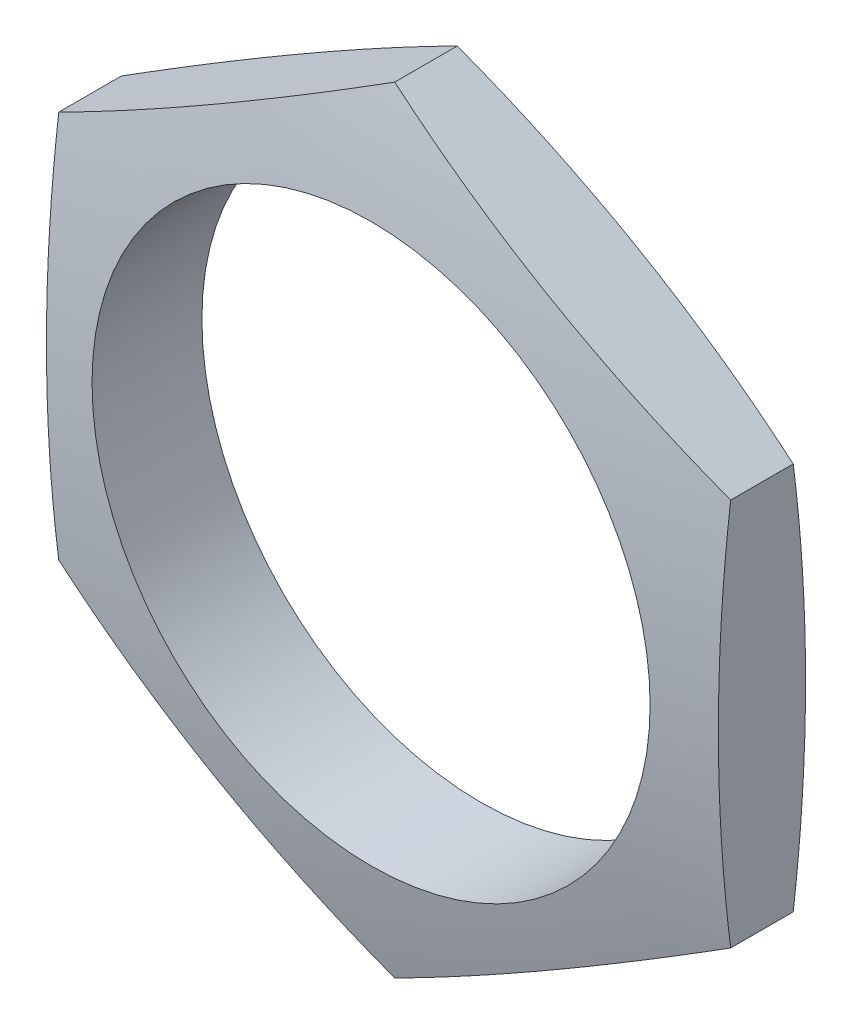
SolidWorks part; units mm, degrees
material "Nickel"
ref_plane "Front Plane" through (0, 0, 0) normal (0, 0, 1) x (1, 0, 0)
ref_plane "Top Plane" through (0, 0, 0) normal (0, 1, 0) x (1, 0, 0)
ref_plane "Right Plane" through (0, 0, 0) normal (1, 0, 0) x (0, 0, -1)
sketch "Sketch1" plane through (0, 0, 0) normal (0, 0, 1) x (1, 0, 0)
  line L1 (0, 8) -> (-6.9282, 4)
  line L2 (-6.9282, 4) -> (-6.9282, -4)
  line L3 (-6.9282, -4) -> (0, -8)
  line L4 (0, -8) -> (6.9282, -4)
  line L5 (6.9282, -4) -> (6.9282, 4)
  line L6 (6.9282, 4) -> (0, 8)
  circle A0 centre (0, 0) radius 6.9282 construction
  dimension "D1" = 16
extrude "Boss-Extrude1" add sketch "Sketch1" along normal blind 2.8
hole_wizard "1/2-20 Tapped Hole1" positions "Sketch2" profile "Sketch4" tap size "1/2-20" standard "ANSI Inch" end condition through all
sketch "Sketch2" plane through (0, 0, 2.8) normal (0, 0, 1) x (1, 0, 0)
  point P0 (0, 0)
sketch "Sketch4" plane through (0, 0, 2.8) normal (1, 0, 0) x (0, -1, 0)
  line L0 (0, 0) -> (0, 2.8)
  line L1 (0, 2.8) -> (5.7544, 2.8)
  line L2 (5.7544, 2.8) -> (5.7544, 0)
  line L5 (5.7544, 0) -> (0, 0)
  line L11 (0, -6.35) -> (0, 107.95) construction
  dimension "Thru Tap Drill Dia." = 11.5087
  dimension "Thru Tap Drill Depth" = 2.8
cosmetic thread "Hole Thread1" parameters "D2"=12.7
sketch "Sketch6" plane through (0, 0, 0) normal (1, 0, 0) x (0, 0, -1)
  line L0 (-2.8, -8) -> (0, -8) construction
  line L2 (-1.4, -4) -> (-1.4, -9.6762) construction
  line L3 (-2.8, -4) -> (0, -4) construction
  line L4 (-3.5568, -8.1692) -> (-3.1419, -1.5102)
  line L5 (-3.0126, -1.5102) -> (-3.1419, -1.5102)
  line L6 (0, 0) -> (-3.6193, 0) construction
  line L7 (1.54, 0) -> (-1.54, 0) construction
  line L8 (0.2126, -1.5102) -> (0.3419, -1.5102)
  line L9 (0.7568, -8.1692) -> (0.3419, -1.5102)
  arc A0 (-2.045, -8) -> (-3.0126, -1.5102) centre (29.365, 0) cw
  arc A1 (-2.045, -8) -> (-3.5568, -8.1692) centre (-2.7891, -8.1895) cw
  arc A2 (-0.755, -8) -> (0.2126, -1.5102) centre (-32.165, 0) ccw
  arc A3 (-0.755, -8) -> (0.7568, -8.1692) centre (-0.0109, -8.1895) ccw
revolve "Cut-Revolve4" cut sketch "Sketch6" angle 360 about L6
